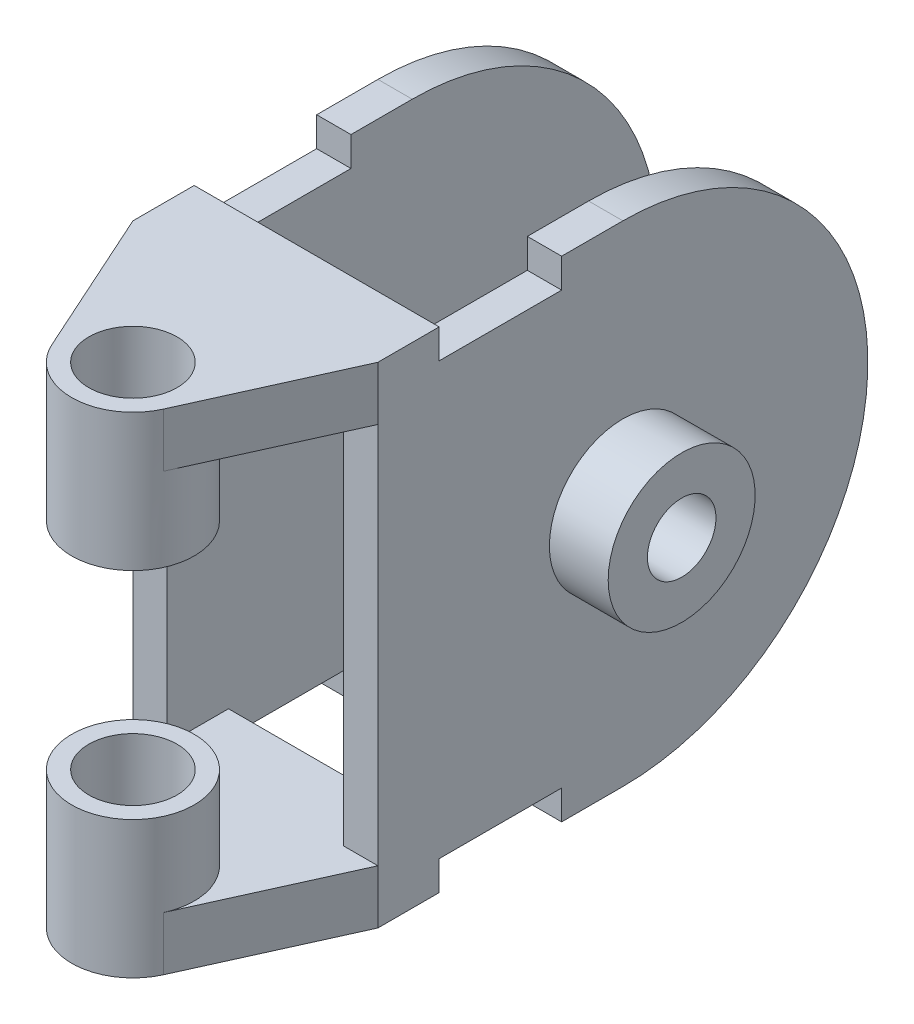
SolidWorks part; units mm, degrees
ref_plane "Front Plane" through (0, 0, 0) normal (0, 0, 1) x (1, 0, 0)
ref_plane "Top Plane" through (0, 0, 0) normal (0, 1, 0) x (1, 0, 0)
ref_plane "Right Plane" through (0, 0, 0) normal (1, 0, 0) x (0, 0, -1)
sketch "Sketch1" plane through (0, 0, 0) normal (1, 0, 0) x (0, 0, -1)
  line L0 (0, 0) -> (12.5, 0)
  line L1 (12.5, 0) -> (12.5, 6)
  line L2 (12.5, 6) -> (37.5, 6)
  line L3 (37.5, 6) -> (37.5, 0)
  line L4 (37.5, 0) -> (50, 0)
  line L5 (50, 100) -> (37.5, 100)
  line L6 (37.5, 100) -> (37.5, 94)
  line L7 (37.5, 94) -> (12.5, 94)
  line L8 (12.5, 94) -> (12.5, 100)
  line L9 (12.5, 100) -> (0, 100)
  line L10 (0, 100) -> (0, 0)
  line L11 (0, 0) -> (0, 128.7719) construction
  arc A0 (50, 0) -> (50, 100) centre (50, 50) ccw
  point P9 (12.8179, 0)
  dimension "D1" = 50
  dimension "D2" = 50
  dimension "D3" = 25
  dimension "D4" = 6
  dimension "D5" = 12.5
extrude "Boss-Extrude1" add sketch "Sketch1" along normal blind 7 from offset 18
sketch "Sketch3" plane through (0, 0, 0) normal (1, 0, 0) x (0, 0, -1)
  line L11 (0, 100) -> (0, 0)
  line L12 (0, 0) -> (12.5, 0)
  line L13 (12.5, 0) -> (12.5, 6)
  line L14 (12.5, 6) -> (37.5, 6)
  line L15 (37.5, 6) -> (37.5, 0)
  line L16 (37.5, 0) -> (50, 0)
  line L17 (50, 100) -> (37.5, 100)
  line L18 (37.5, 100) -> (37.5, 94)
  line L19 (37.5, 94) -> (12.5, 94)
  line L20 (12.5, 94) -> (12.5, 100)
  line L21 (12.5, 100) -> (0, 100)
  line L22 (0, 100) -> (0, 0)
  line L23 (0, 0) -> (12.5, 0)
  line L24 (12.5, 0) -> (12.5, 6)
  line L25 (12.5, 6) -> (37.5, 6)
  line L26 (37.5, 6) -> (37.5, 0)
  line L27 (37.5, 0) -> (50, 0)
  line L28 (50, 100) -> (37.5, 100)
  line L29 (37.5, 100) -> (37.5, 94)
  line L30 (37.5, 94) -> (12.5, 94)
  line L31 (12.5, 94) -> (12.5, 100)
  line L32 (12.5, 100) -> (0, 100)
  arc A1 (50, 0) -> (50, 100) centre (50, 50) ccw
  arc A2 (50, 0) -> (50, 100) centre (50, 50) ccw
  dimension "D1" = 0
extrude "Boss-Extrude3" add sketch "Sketch3" against normal blind 7 from offset 18 separate body offset against normal yes
sketch "Sketch5" plane through (0, 100, 0) normal (0, 1, 0) x (1, 0, 0)
  line L0 (-25, 12.5) -> (25, 12.5)
  line L1 (25, 12.5) -> (25, 0)
  line L2 (-25, 12.5) -> (-25, 0)
  line L3 (-25, 12.5) -> (-25, 0) construction
  line L4 (25, 0) -> (11.393, -30.143)
  line L5 (-25, 0) -> (-11.393, -30.143)
  line L6 (-25, 0) -> (-18, 0) construction
  arc A0 (-11.393, -30.143) -> (11.393, -30.143) centre (0, -25) ccw
  point P10 (0, -25)
  point P11 (0, 0)
  point P18 (0, 0)
  point P20 (0, 0)
  dimension "D1" = 25
  dimension "D2" = 25
extrude "Boss-Extrude4" add sketch "Sketch5" against normal blind 11 contours L5 A0 L4 L1 L0 L2
sketch "Sketch8" plane through (0, 0, 0) normal (0, -1, 0) x (1, 0, 0)
  line L0 (-25, 0) -> (-25, -12.5)
  line L1 (-25, -12.5) -> (-18, -12.5)
  line L2 (25, 0) -> (25, -12.5)
  line L3 (25, -12.5) -> (18, -12.5)
  line L7 (-11.393, 30.143) -> (-25, 0)
  line L8 (-25, 0) -> (-18, 0)
  line L9 (-18, 0) -> (-18, -12.5)
  line L10 (-18, -12.5) -> (18, -12.5)
  line L11 (18, -12.5) -> (18, 0)
  line L12 (18, 0) -> (25, 0)
  line L13 (25, 0) -> (11.393, 30.143)
  line L14 (-11.393, 30.143) -> (-25, 0)
  line L17 (-18, -12.5) -> (18, -12.5)
  line L20 (25, 0) -> (11.393, 30.143)
  arc A1 (11.393, 30.143) -> (-11.393, 30.143) centre (0, 25) ccw
  arc A2 (11.393, 30.143) -> (-11.393, 30.143) centre (0, 25) ccw
  dimension "D1" = 0
extrude "Boss-Extrude5" add sketch "Sketch8" against normal blind 11
sketch "Sketch9" plane through (0, 100, 0) normal (0, 1, 0) x (1, 0, 0)
  circle A0 centre (0, -25) radius 12.5
  dimension "D1" = 25
extrude "Boss-Extrude6" add sketch "Sketch9" against normal blind 28
sketch "Sketch11" plane through (0, 0, 0) normal (0, -1, 0) x (1, 0, 0)
  circle A0 centre (0, 25) radius 12.5
  arc A1 (11.393, 30.143) -> (-11.393, 30.143) centre (0, 25) ccw construction
extrude "Boss-Extrude7" add sketch "Sketch11" against normal blind 28
hole_wizard "Hole1" positions "Sketch12" profile "Sketch13" legacy end condition through all
sketch "Sketch12" plane through (0, 0, 0) normal (0, -1, 0) x (-1, 0, 0)
  point P0 (0, -25)
sketch "Sketch13" plane through (0, 0, 25) normal (1, 0, 0) x (0, 0, -1)
  line L0 (0, 0) -> (0, 100)
  line L1 (0, 100) -> (9, 100)
  line L2 (9, 100) -> (9, 0)
  line L3 (9, 0) -> (0, 0)
  line L4 (0, 110) -> (0, -10) construction
  dimension "Diameter" = 18
  dimension "Depth" = 100
sketch "Sketch14" plane through (-25, 0, 0) normal (-1, 0, 0) x (0, 0, 1)
  circle A0 centre (-50, 50) radius 15
  dimension "D1" = 30
extrude "Boss-Extrude8" add sketch "Sketch14" along normal blind 12
mirror "Mirror1" about plane through (0, 0, 0) normal (1, 0, 0) of "Boss-Extrude8"
hole_wizard "Hole2" positions "Sketch15" profile "Sketch16" legacy end condition through all
sketch "Sketch15" plane through (37, 0, 0) normal (1, 0, 0) x (0, 0, -1)
  point P0 (50, 50)
sketch "Sketch16" plane through (37, 50, -50) normal (0, 1, 0) x (0, 0, -1)
  line L0 (0, 0) -> (0, 74)
  line L1 (0, 74) -> (7, 74)
  line L2 (7, 74) -> (7, 0)
  line L3 (7, 0) -> (0, 0)
  line L4 (0, 110) -> (0, -10) construction
  dimension "Diameter" = 14
  dimension "Depth" = 74
